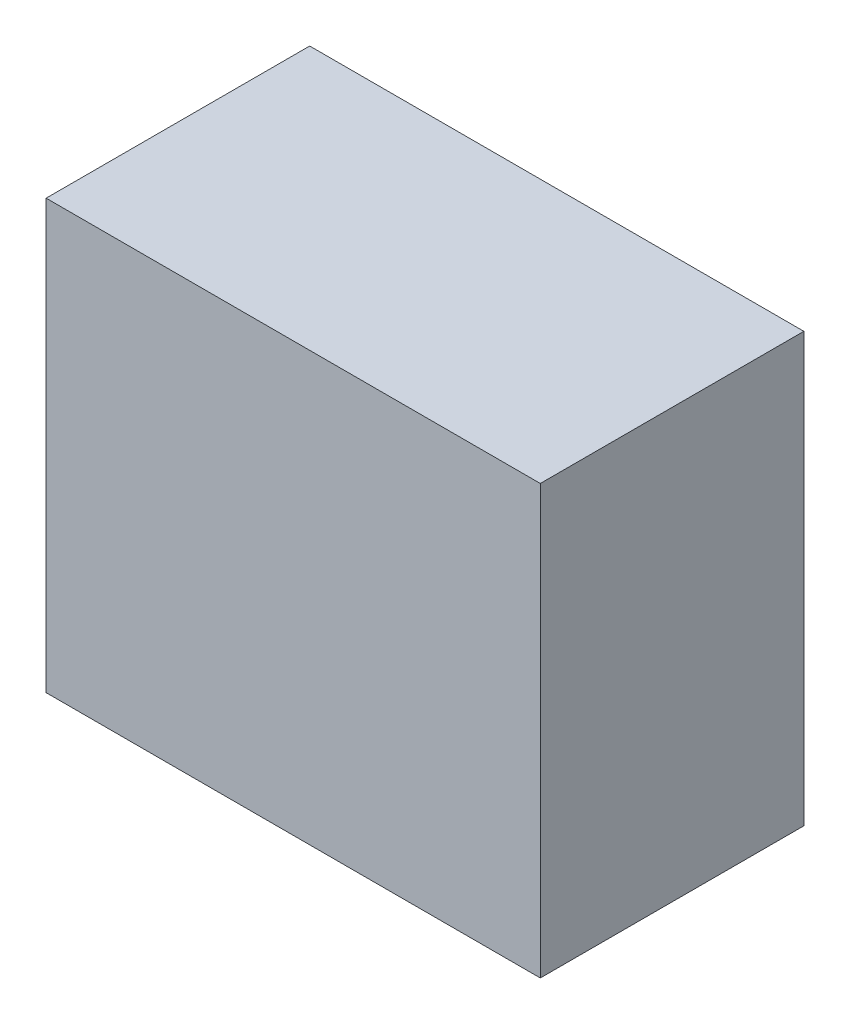
SolidWorks part; units mm, degrees
ref_plane "Front Plane" through (0, 0, 0) normal (0, 0, 1) x (1, 0, 0)
ref_plane "Top Plane" through (0, 0, 0) normal (0, 1, 0) x (1, 0, 0)
ref_plane "Right Plane" through (0, 0, 0) normal (1, 0, 0) x (0, 0, -1)
sketch "Sketch1" plane through (0, 0, 0) normal (0, 0, 1) x (1, 0, 0)
  line L1 (-482.1713, -309.7305) -> (-863.1713, -309.7305)
  line L2 (-482.1713, -309.7305) -> (-482.1713, 20.4695)
  line L3 (-482.1713, 20.4695) -> (-863.1713, 20.4695)
  line L4 (-863.1713, -309.7305) -> (-863.1713, 20.4695)
  point P4 (-672.6713, 20.4695)
  dimension "D1" = 381
  dimension "D2" = 330.2
extrude "Boss-Extrude1" add sketch "Sketch1" along normal blind 203.2
